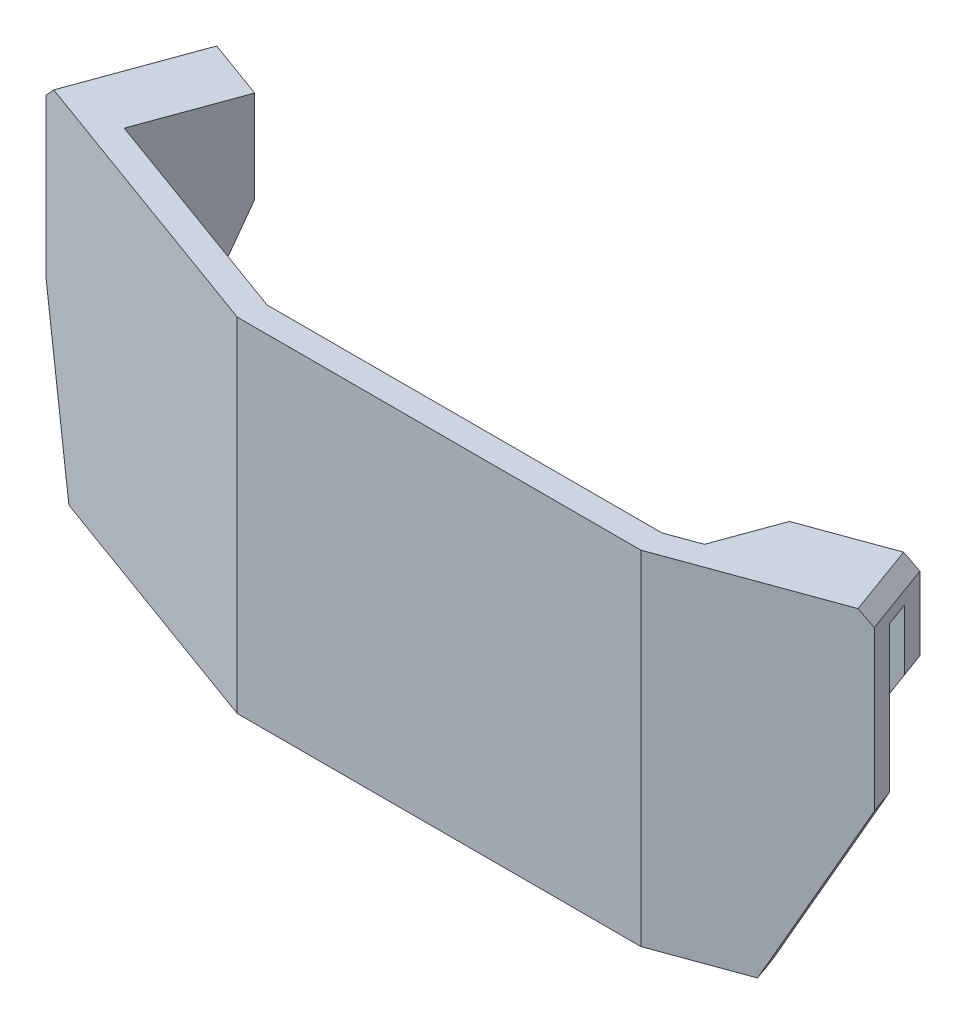
SolidWorks part; units mm, degrees
ref_plane "Front Plane" through (0, 0, 0) normal (0, 0, 1) x (1, 0, 0)
ref_plane "Top Plane" through (0, 0, 0) normal (0, 1, 0) x (1, 0, 0)
ref_plane "Right Plane" through (0, 0, 0) normal (1, 0, 0) x (0, 0, -1)
sketch "Sketch8" plane through (0, 0, 0) normal (0, 1, 0) x (1, 0, 0)
  line L0 (19.7614, 5.7997) -> (27.279, 8.5358)
  line L1 (27.279, 8.5358) -> (29.3311, 2.8977)
  line L2 (15.8748, -2) -> (29.3311, 2.8977)
  line L4 (17.9755, 0.893) -> (15.5222, 0)
  line L5 (19.7614, 5.7997) -> (17.9755, 0.893)
  line L8 (-15.8748, -2) -> (15.8748, -2)
  line L9 (-33.1794, 6.4267) -> (-15.5222, 0)
  line L10 (-39.5016, 6.5995) -> (-15.8748, -2)
  line L11 (-39.5016, 6.5995) -> (-36.0814, 15.9964)
  line L12 (-36.0814, 15.9964) -> (-30.4432, 13.9443)
  line L13 (-30.4432, 13.9443) -> (-33.1794, 6.4267)
  line L14 (-15.5222, 0) -> (15.5222, 0)
  point P4 (0, 0)
  point P5 (0, 0)
  dimension "D1" = 31.0443
  dimension "D2" = 31.7496
  dimension "D3" = 14.3199
  dimension "D4" = 6
  dimension "D5" = 6
  dimension "D6" = 8
  dimension "D7" = 8
  dimension "D8" = 5.2216
  dimension "D9" = 2
  dimension "D10" = 2
  dimension "D11" = 2.6108
  dimension "D12" = 160
  dimension "D13" = 110
  dimension "D14" = 160
  dimension "D15" = 70
  dimension "D16" = 25.1431
  dimension "D17" = 18.7905
  dimension "D18" = 10
  dimension "D19" = 29.3311
  dimension "D20" = 15.9964
extrude "Boss-Extrude4" add sketch "Sketch8" along normal blind 2
sketch "Sketch12" plane through (0, 0, 0) normal (0, -1, 0) x (1, 0, 0)
  line L0 (-39.5016, -6.5995) -> (-15.8748, 2)
  line L1 (-15.8748, 2) -> (15.8748, 2)
  line L2 (15.8748, 2) -> (29.3311, -2.8977)
  line L5 (-15.5222, 0) -> (15.5222, 0)
  line L9 (-36.0814, -15.9964) -> (-39.5016, -6.5995) construction
  line L10 (-38.8176, -8.4788) -> (-39.5016, -6.5995)
  line L12 (-38.8176, -8.4788) -> (-33.1794, -6.4267)
  line L13 (-33.1794, -6.4267) -> (-15.5222, 0)
  line L16 (15.5222, 0) -> (17.9755, -0.893)
  line L17 (17.9755, -0.893) -> (28.647, -4.7771)
  line L18 (29.3311, -2.8977) -> (27.279, -8.5358) construction
  line L19 (28.647, -4.7771) -> (29.3311, -2.8977)
extrude "Boss-Extrude7" add sketch "Sketch12" along normal blind 25
sketch "Sketch13" plane through (0, 0, 0) normal (0, -1, 0) x (1, 0, 0)
  line L3 (-30.4432, -13.9443) -> (-36.0814, -15.9964) construction
  line L4 (-34.202, -15.3123) -> (-36.0814, -15.9964)
  line L9 (-32.3226, -14.6283) -> (-30.4432, -13.9443)
  line L11 (19.7614, -5.7997) -> (27.279, -8.5358)
  line L12 (27.279, -8.5358) -> (27.963, -6.6565)
  line L13 (28.647, -4.7771) -> (27.279, -8.5358) construction
  line L14 (27.963, -6.6565) -> (18.8685, -3.3463)
  line L15 (19.7614, -5.7997) -> (17.9755, -0.893) construction
  line L16 (18.8685, -3.3463) -> (19.7614, -5.7997)
  line L22 (-36.0814, -15.9964) -> (-38.1335, -10.3582)
  line L23 (-36.0814, -15.9964) -> (-38.8176, -8.4788) construction
  line L24 (-38.1335, -10.3582) -> (-36.2541, -9.6742)
  line L25 (-36.2541, -9.6742) -> (-34.202, -15.3123)
  line L26 (-38.8176, -8.4788) -> (-15.5222, 0) construction
  line L27 (-32.3226, -14.6283) -> (-35.0588, -7.1108)
  line L28 (-35.0588, -7.1108) -> (-33.1794, -6.4267)
  line L29 (-33.1794, -6.4267) -> (-30.4432, -13.9443)
  dimension "D1" = 2
  dimension "D2" = 2
  dimension "D4" = 2
extrude "Boss-Extrude8" add sketch "Sketch13" along normal blind 11.5
sketch "Sketch15" plane through (0.4477, 0, 1.23) normal (-0.342, 0, -0.9397) x (-0.9397, 0, 0.342)
  line L0 (-24.5533, -11.5) -> (-28.5533, -4.75)
  line L1 (-20.5533, -11.5) -> (-28.5533, -11.5) construction
  line L2 (-28.5533, 2) -> (-28.5533, -11.5) construction
  line L3 (-28.5533, -4.75) -> (-28.5533, -11.5)
  line L4 (-28.5533, -11.5) -> (-24.5533, -11.5)
extrude "Cut-Extrude4" cut sketch "Sketch15" against normal up to surface (2 mm away) up to face at (23.4157, -5.75, -5.0014)
sketch "Sketch16" plane through (2.4998, 0, 6.8681) normal (0.342, 0, 0.9397) x (0.9397, 0, -0.342)
  line L0 (21.3933, -25) -> (28.5533, -11.5)
  line L1 (28.5533, -25) -> (14.2334, -25) construction
  line L2 (28.5533, 2) -> (28.5533, -25) construction
  line L3 (28.5533, -11.5) -> (28.5533, -25)
  line L4 (28.5533, -25) -> (21.3933, -25)
extrude "Cut-Extrude5" cut sketch "Sketch16" against normal up to surface (2 mm away) up to face at (20.7149, -7.6667, -1.89)
sketch "Sketch17" plane through (-2.4998, 0, 6.8681) normal (-0.342, 0, 0.9397) x (0.9397, 0, 0.342)
  line L1 (-39.3765, 2) -> (-39.3765, -25) construction
  line L4 (-39.3765, -25) -> (-39.3765, -11.5)
  line L5 (-39.3765, -25) -> (-36.3765, -25)
  line L6 (-14.2334, -25) -> (-39.3765, -25) construction
  line L7 (-36.3765, -25) -> (-39.3765, -11.5)
  dimension "D1" = 3
extrude "Cut-Extrude6" cut sketch "Sketch17" against normal up to surface (2 mm away) up to face at (-30.6445, -8.625, -5.5041)
chamfer "Chamfer2" distance 1 angle 45 2 edges at (28.305, 2, -5.7168) (-37.7915, 2, -11.2979)
sketch "Sketch23" plane through (-37.0018, 0, -13.4676) normal (-0.9397, 0, -0.342) x (-0.342, 0, 0.9397)
  line L0 (0.3089, -11.5) -> (-2.6911, -5.25)
  line L1 (3.3089, -11.5) -> (-2.6911, -11.5) construction
  line L2 (-2.6911, 1) -> (-2.6911, -11.5) construction
  line L3 (-2.6911, -5.25) -> (-2.6911, -11.5)
  line L4 (-2.6911, -11.5) -> (0.3089, -11.5)
extrude "Cut-Extrude8" cut sketch "Sketch23" against normal up to surface (6 mm away) up to face at (-31.8113, -4.75, -10.1855)
